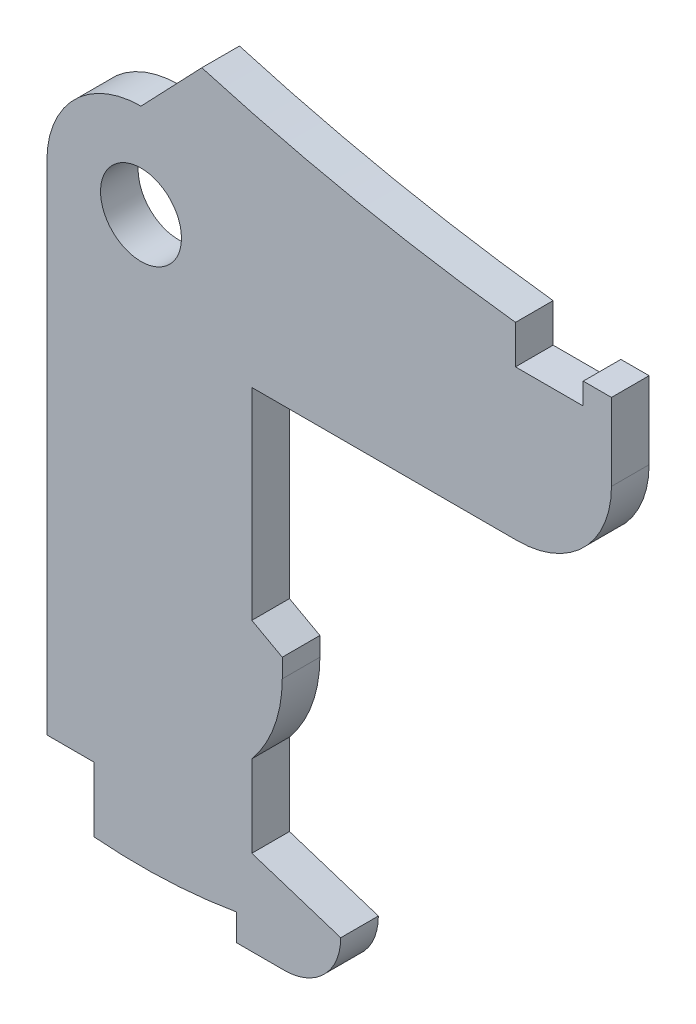
SolidWorks part; units mm, degrees
ref_plane "정면" through (0, 0, 0) normal (0, 0, 1) x (1, 0, 0)
ref_plane "윗면" through (0, 0, 0) normal (0, 1, 0) x (1, 0, 0)
ref_plane "우측면" through (0, 0, 0) normal (1, 0, 0) x (0, 0, -1)
sketch "스케치1" plane through (0, 0, 0) normal (0, 0, 1) x (1, 0, 0)
  line L0 (28.1634, -41.2491) -> (23.65, -39.725)
  line L1 (17.6552, -8.2873) -> (21.1871, -4.904)
  line L2 (53.4867, -33.1492) -> (56.7186, -29.7659)
  line L3 (59.3761, -60.24) -> (59.3761, -64.5868)
  line L4 (73.3867, -33.1492) -> (73.3867, -35.1985)
  line L5 (73.3867, -35.1985) -> (76.9867, -35.1985)
  line L6 (76.9867, -35.1985) -> (76.9867, -34.0533)
  line L7 (76.9867, -34.0533) -> (78.4867, -34.0533)
  line L8 (78.4867, -34.0533) -> (78.4867, -38.1492)
  line L9 (73.4867, -43.1492) -> (59.3761, -43.1492)
  line L10 (59.3761, -43.1492) -> (59.3761, -53.868)
  line L11 (58.5629, -69.1109) -> (61.1004, -69.1109)
  line L12 (48.4867, -64.5869) -> (48.4867, -38.1492)
  line L15 (37.5552, -8.5081) -> (37.5552, -10.3366)
  line L16 (37.5552, -10.3366) -> (41.1552, -10.3366)
  line L18 (50.9867, -68.0237) -> (50.9867, -64.5869)
  line L19 (50.9867, -64.5869) -> (48.4867, -64.5869)
  line L20 (41.1552, -10.3366) -> (41.1552, -9.1914)
  line L21 (41.1552, -9.1914) -> (42.6552, -9.1914)
  line L22 (42.6552, -9.1914) -> (42.6552, -13.2873)
  line L23 (37.6552, -18.2873) -> (23.65, -18.2873)
  line L24 (23.65, -18.2873) -> (23.65, -39.725)
  line L25 (22.7313, -44.2491) -> (25.1634, -44.2491)
  line L26 (12.6552, -39.725) -> (12.6552, -13.2873)
  line L27 (58.5629, -67.6952) -> (58.5629, -69.1109)
  line L28 (59.3761, -60.24) -> (59.3761, -64.5868)
  line L31 (59.3761, -60.24) -> (59.3761, -64.5868)
  line L32 (60.9929, -55.7531) -> (60.9929, -54.7553)
  line L33 (15.1552, -43.1618) -> (15.1552, -39.725)
  line L34 (15.1552, -39.725) -> (12.6552, -39.725)
  line L35 (22.7313, -42.8333) -> (22.7313, -44.2491)
  line L36 (60.9929, -54.7553) -> (59.3761, -53.868)
  line L40 (64.1004, -66.1109) -> (59.3761, -64.5868)
  arc A0 (37.3363, -8.2601) -> (37.5552, -8.5081) centre (37.3052, -8.5081) cw
  arc A1 (25.1634, -44.2491) -> (28.1634, -41.2491) centre (25.1634, -41.2491) ccw
  circle A2 centre (53.4867, -38.1492) radius 2.15
  circle A3 centre (17.6552, -13.2873) radius 2.5
  arc A4 (53.4867, -33.1492) -> (48.4867, -38.1492) centre (53.4867, -38.1492) ccw
  arc A5 (50.9867, -68.0237) -> (58.5629, -67.6952) centre (53.4867, -38.1492) ccw
  arc A6 (17.6552, -8.2873) -> (12.6552, -13.2873) centre (17.6552, -13.2873) ccw
  arc A7 (15.1552, -43.1618) -> (22.7313, -42.8333) centre (17.6552, -13.2873) ccw
  arc A9 (37.3363, -8.2601) -> (21.1871, -4.904) centre (50.2016, 94.181) cw
  arc A10 (42.6552, -13.2873) -> (37.6552, -18.2873) centre (37.6552, -13.2873) cw
  arc A11 (73.3867, -33.1492) -> (56.7186, -29.7659) centre (85.5208, 69.3811) cw
  arc A12 (78.4867, -38.1492) -> (73.4867, -43.1492) centre (73.4867, -38.1492) cw
  arc A13 (60.9929, -55.7531) -> (59.3761, -60.24) centre (53.9584, -55.7531) cw
  arc A14 (61.1004, -69.1109) -> (64.1004, -66.1109) centre (61.1004, -66.1109) ccw
  point P4 (37.5552, -8.2873)
  dimension "D1" = 3.6
  dimension "D2" = 1.5
  dimension "D3" = 103.2458
  dimension "D5" = 5
  dimension "D6" = 5
  dimension "D4" = 0.25
  dimension "D8" = 3
  dimension "D9" = 4.3
  dimension "D10" = 5
  dimension "D13" = 3
  dimension "D7" = 30
  dimension "D11" = 30
  dimension "D12" = 1.5
  dimension "D14" = 2.5
  dimension "D17" = 3.6
extrude "보스-돌출1" add sketch "스케치1" along normal blind 2 contours L11 A14 L40 L3 A13 L32 L36 L10 L9 A12 L8 L7 L6 L5 L4 A11 L2 A4 L12 L19 L18 A5 L27 A2
